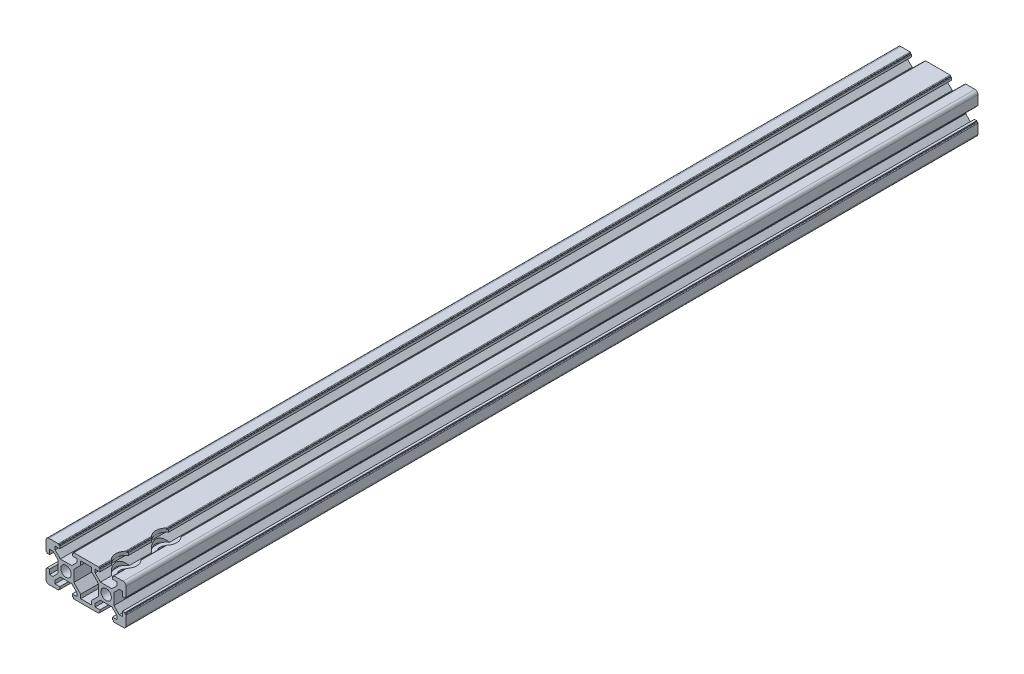
SolidWorks part; units mm, degrees
ref_plane "前视基准面" through (0, 0, 0) normal (0, 0, 1) x (1, 0, 0)
ref_plane "上视基准面" through (0, 0, 0) normal (0, 1, 0) x (1, 0, 0)
ref_plane "右视基准面" through (0, 0, 0) normal (1, 0, 0) x (0, 0, -1)
sketch "草图1" plane through (0, 0, 0) normal (0, 0, 1) x (1, 0, 0)
  line L0 (0, 0) -> (0, -41497.3383) construction
  line L1 (0, 0) -> (41497.3383, 0) construction
  line L2 (-13.9, 0) -> (-13.9, 2.8393)
  line L3 (-13.9, 2.8393) -> (-16.5607, 5.5)
  line L4 (-16.5607, 5.5) -> (-18.2, 5.5)
  line L5 (-18.2, 5.5) -> (-18.2, 3.1)
  line L6 (-18.2, 3.1) -> (-19.4, 3.1)
  line L7 (-19.4, 3.1) -> (-19.4, 3.6)
  line L8 (-19.4, 3.6) -> (-20, 3.6)
  line L9 (-20, 3.6) -> (-20, 10)
  line L10 (-20, 10) -> (-13.6, 10)
  line L11 (-13.6, 10) -> (-13.6, 9.4)
  line L12 (-13.6, 9.4) -> (-13.1, 9.4)
  line L13 (-13.1, 9.4) -> (-13.1, 8.2)
  line L14 (-13.1, 8.2) -> (-15.5, 8.2)
  line L15 (-15.5, 6.5607) -> (-12.8393, 3.9)
  line L16 (-12.8393, 3.9) -> (-7.1607, 3.9)
  line L17 (-4.5, 6.5607) -> (-7.1607, 3.9)
  line L18 (-4.5, 6.5607) -> (-4.5, 8.2)
  line L19 (-4.5, 8.2) -> (-6.9, 8.2)
  line L20 (-6.9, 8.2) -> (-6.9, 9.4)
  line L21 (-6.9, 9.4) -> (-6.4, 9.4)
  line L22 (-6.4, 9.4) -> (-6.4, 10)
  line L23 (-6.4, 10) -> (6.4, 10)
  line L24 (-15.5, 8.2) -> (-15.5, 6.5607)
  line L25 (-10, 0) -> (-20, 10) construction
  line L26 (-6.1, -2.8393) -> (-6.1, 2.8393)
  line L27 (-6.1, 2.8393) -> (-2.7, 6.2393)
  line L28 (-2.7, 6.2393) -> (-2.7, 8.2)
  line L29 (-2.7, 8.2) -> (2.7, 8.2)
  line L30 (-10, 0) -> (0, 10) construction
  line L31 (13.9, 0) -> (13.9, 2.8393)
  line L32 (6.1, -2.8393) -> (6.1, 2.8393)
  line L33 (4.5, 6.5607) -> (7.1607, 3.9)
  line L34 (12.8393, 3.9) -> (7.1607, 3.9)
  line L35 (6.1, 2.8393) -> (2.7, 6.2393)
  line L36 (2.7, 6.2393) -> (2.7, 8.2)
  line L37 (4.5, 6.5607) -> (4.5, 8.2)
  line L38 (6.4, 9.4) -> (6.4, 10)
  line L39 (6.9, 9.4) -> (6.4, 9.4)
  line L40 (6.9, 8.2) -> (6.9, 9.4)
  line L41 (4.5, 8.2) -> (6.9, 8.2)
  line L42 (13.1, 9.4) -> (13.1, 8.2)
  line L43 (13.6, 9.4) -> (13.1, 9.4)
  line L44 (13.6, 10) -> (13.6, 9.4)
  line L45 (20, 10) -> (13.6, 10)
  line L46 (20, 3.6) -> (20, 10)
  line L47 (19.4, 3.6) -> (20, 3.6)
  line L48 (19.4, 3.1) -> (19.4, 3.6)
  line L49 (18.2, 3.1) -> (19.4, 3.1)
  line L50 (18.2, 5.5) -> (18.2, 3.1)
  line L51 (16.5607, 5.5) -> (18.2, 5.5)
  line L52 (13.9, 2.8393) -> (16.5607, 5.5)
  line L53 (15.5, 6.5607) -> (12.8393, 3.9)
  line L54 (15.5, 8.2) -> (15.5, 6.5607)
  line L55 (13.1, 8.2) -> (15.5, 8.2)
  line L56 (15.5, -6.5607) -> (12.8393, -3.9)
  line L57 (13.9, -2.8393) -> (16.5607, -5.5)
  line L58 (16.5607, -5.5) -> (18.2, -5.5)
  line L59 (18.2, -5.5) -> (18.2, -3.1)
  line L60 (18.2, -3.1) -> (19.4, -3.1)
  line L61 (19.4, -3.1) -> (19.4, -3.6)
  line L62 (19.4, -3.6) -> (20, -3.6)
  line L63 (12.8393, -3.9) -> (7.1607, -3.9)
  line L64 (13.9, 0) -> (13.9, -2.8393)
  line L65 (13.1, -8.2) -> (15.5, -8.2)
  line L66 (15.5, -8.2) -> (15.5, -6.5607)
  line L67 (20, -3.6) -> (20, -10)
  line L68 (20, -10) -> (13.6, -10)
  line L69 (13.6, -10) -> (13.6, -9.4)
  line L70 (13.6, -9.4) -> (13.1, -9.4)
  line L71 (13.1, -9.4) -> (13.1, -8.2)
  line L72 (4.5, -8.2) -> (6.9, -8.2)
  line L73 (6.9, -8.2) -> (6.9, -9.4)
  line L74 (6.9, -9.4) -> (6.4, -9.4)
  line L75 (6.4, -9.4) -> (6.4, -10)
  line L76 (4.5, -6.5607) -> (4.5, -8.2)
  line L77 (2.7, -6.2393) -> (2.7, -8.2)
  line L78 (6.1, -2.8393) -> (2.7, -6.2393)
  line L79 (4.5, -6.5607) -> (7.1607, -3.9)
  line L80 (-2.7, -8.2) -> (2.7, -8.2)
  line L81 (-2.7, -6.2393) -> (-2.7, -8.2)
  line L82 (-6.1, -2.8393) -> (-2.7, -6.2393)
  line L83 (-4.5, -6.5607) -> (-7.1607, -3.9)
  line L84 (-4.5, -8.2) -> (-6.9, -8.2)
  line L85 (-4.5, -6.5607) -> (-4.5, -8.2)
  line L86 (-6.4, -10) -> (6.4, -10)
  line L87 (-6.4, -9.4) -> (-6.4, -10)
  line L88 (-6.9, -9.4) -> (-6.4, -9.4)
  line L89 (-6.9, -8.2) -> (-6.9, -9.4)
  line L90 (-13.1, -9.4) -> (-13.1, -8.2)
  line L91 (-13.6, -9.4) -> (-13.1, -9.4)
  line L92 (-13.6, -10) -> (-13.6, -9.4)
  line L93 (-15.5, -8.2) -> (-15.5, -6.5607)
  line L94 (-13.1, -8.2) -> (-15.5, -8.2)
  line L95 (-12.8393, -3.9) -> (-7.1607, -3.9)
  line L96 (-15.5, -6.5607) -> (-12.8393, -3.9)
  line L97 (-13.9, 0) -> (-13.9, -2.8393)
  line L98 (-13.9, -2.8393) -> (-16.5607, -5.5)
  line L99 (-19.4, -3.6) -> (-20, -3.6)
  line L100 (-19.4, -3.1) -> (-19.4, -3.6)
  line L101 (-18.2, -3.1) -> (-19.4, -3.1)
  line L102 (-18.2, -5.5) -> (-18.2, -3.1)
  line L103 (-16.5607, -5.5) -> (-18.2, -5.5)
  line L104 (-20, -3.6) -> (-20, -10)
  line L105 (-20, -10) -> (-13.6, -10)
  circle A0 centre (-10, 0) radius 2.6
  circle A1 centre (10, 0) radius 2.6
  point P50 (0, 8.2)
  point P95 (6.1, 0)
  point P96 (-6.1, 0)
  dimension "D1" = 5.2
  dimension "D2" = 45
  dimension "D3" = 1.5
  dimension "D4" = 20
  dimension "D5" = 40
  dimension "D6" = 0.75
  dimension "D7" = 7.2
  dimension "D8" = 6.2
  dimension "D9" = 6.1
  dimension "D10" = 1.8
  dimension "D11" = 1.2
  dimension "D12" = 12.2
  dimension "D13" = 5.4
  dimension "D14" = 11
  dimension "D15" = 1.5
  dimension "D16" = 0.75
extrude "凸台-拉伸1" add sketch "草图1" along normal mid plane 425
fillet "圆角1" radius 1.5 4 edges at (20, -10, 0) (20, 10, 0) (-20, -10, 0) (-20, 10, 0)
fillet "圆角2" radius 0.3 12 edges at (-6.4, 10, 0) (-13.6, 10, 0) (-20, 3.6, 0) (-20, -3.6, 0) (-13.6, -10, 0) (-6.4, -10, 0) (6.4, -10, 0) (20, -3.6, 0) (20, 3.6, 0) (13.6, -10, 0) (13.6, 10, 0) (6.4, 10, 0)
sketch "草图2" plane through (0, 3.9, 0) normal (0, 1, 0) x (1, 0, 0)
  line L0 (20, 212.5) -> (20, -212.5) construction
  line L1 (12.8393, -212.5) -> (7.1607, -212.5) construction
  circle A0 centre (10, -202.5) radius 3.1
  circle A1 centre (10, -182.5) radius 3.1
  dimension "D1" = 20
  dimension "D2" = 10
  dimension "D3" = 6.2
  dimension "D4" = 10
extrude "切除-拉伸1" cut sketch "草图2" against normal through all both and the other way through all
sketch "草图3" plane through (0, 3.9, 0) normal (0, 1, 0) x (1, 0, 0)
  circle A0 centre (10, -182.5) radius 5.25
  circle A1 centre (10, -202.5) radius 5.25
  dimension "D1" = 10.5
extrude "切除-拉伸2" cut sketch "草图3" along normal through all
equation "\"D6@草图1\"=1/2*\"D3@草图1\""
equation "\"D16@草图1\"=0.5*\"D15@草图1\""
